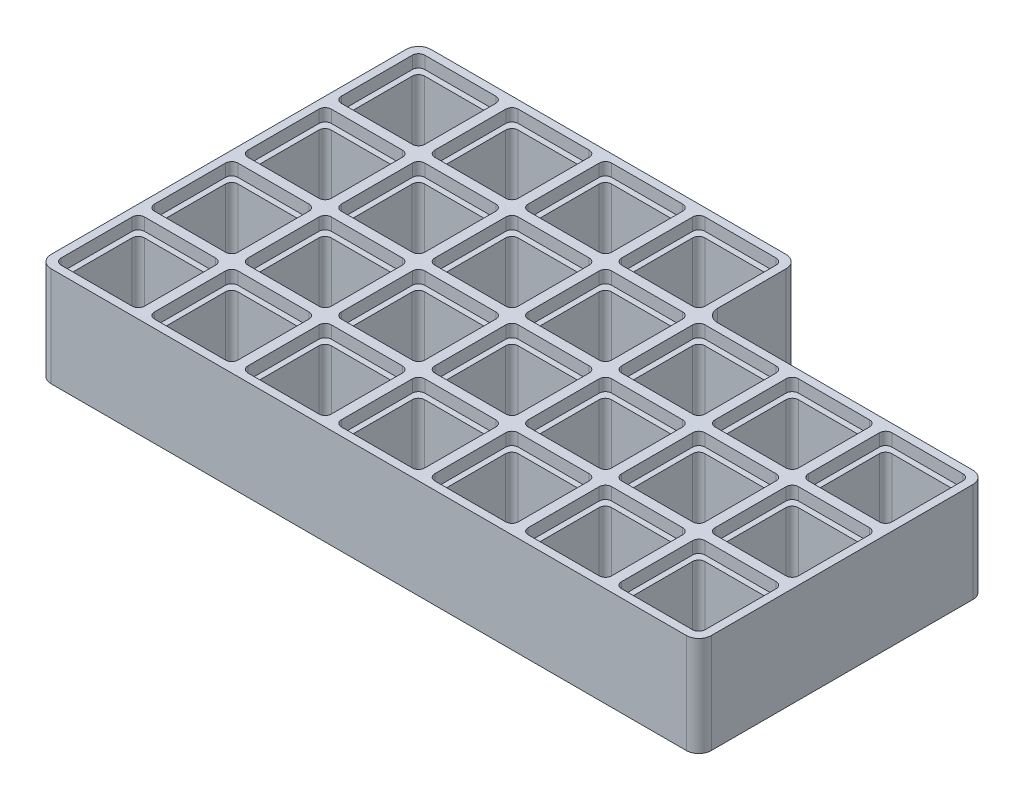
SolidWorks part; units mm, degrees
ref_plane "前视基准面" through (0, 0, 0) normal (0, 0, 1) x (1, 0, 0)
ref_plane "上视基准面" through (0, 0, 0) normal (0, 1, 0) x (1, 0, 0)
ref_plane "右视基准面" through (0, 0, 0) normal (1, 0, 0) x (0, 0, -1)
other "Configuration Table"
sketch "草图1" plane through (0, 0, 0) normal (0, 1, 0) x (1, 0, 0)
  line L0 (-45, 59) -> (-45, 48)
  line L1 (-104, 61) -> (-47, 61)
  line L2 (-106, 59) -> (-106, 2)
  line L3 (-104, 0) -> (-2, 0)
  line L4 (0, 44) -> (0, 2)
  line L9 (-43, 46) -> (-2, 46)
  arc A0 (-106, 2) -> (-104, 0) centre (-104, 2) ccw
  arc A1 (-2, 0) -> (0, 2) centre (-2, 2) ccw
  arc A3 (-104, 61) -> (-106, 59) centre (-104, 59) ccw
  arc A8 (-45, 48) -> (-43, 46) centre (-43, 48) ccw
  arc A9 (-2, 46) -> (0, 44) centre (-2, 44) cw
  arc A10 (-45, 59) -> (-47, 61) centre (-47, 59) ccw
  point P8 (-106, 0)
  point P11 (0, 0)
  point P12 (-45, 46)
  point P14 (0, 61)
  point P17 (-106, 61)
  point P22 (0, 46)
  point P25 (-45, 61)
  dimension "D3" = 2
  dimension "D6" = 2
  dimension "D1" = 106
  dimension "D2" = 61
  dimension "D4" = 45
  dimension "D5" = 15
extrude "凸台-拉伸1" add sketch "草图1" along normal blind 16
sketch "草图3" plane through (0, 0, 0) normal (0, -1, 0) x (1, 0, 0)
  line L0 (-106, -59) -> (-106, -2) construction
  line L1 (-102.8, -2.22) -> (-93.2, -2.22)
  line L2 (-103.8, -3.22) -> (-103.8, -12.78)
  line L3 (-102.8, -13.78) -> (-93.2, -13.78)
  line L4 (-92.2, -3.22) -> (-92.2, -12.78)
  line L5 (-103.8, -2.22) -> (-92.2, -13.78) construction
  line L6 (-103.8, -13.78) -> (-92.2, -2.22) construction
  line L7 (-104, 0) -> (-2, 0) construction
  line L8 (-103.8, -18.22) -> (-103.8, -27.78)
  line L9 (-102.8, -17.22) -> (-93.2, -17.22)
  line L10 (-92.2, -18.22) -> (-92.2, -27.78)
  line L11 (-102.8, -28.78) -> (-93.2, -28.78)
  line L12 (-103.8, -33.22) -> (-103.8, -42.78)
  line L13 (-102.8, -32.22) -> (-93.2, -32.22)
  line L14 (-92.2, -33.22) -> (-92.2, -42.78)
  line L15 (-102.8, -43.78) -> (-93.2, -43.78)
  line L16 (-103.8, -48.22) -> (-103.8, -57.78)
  line L17 (-102.8, -47.22) -> (-93.2, -47.22)
  line L18 (-92.2, -48.22) -> (-92.2, -57.78)
  line L19 (-102.8, -58.78) -> (-93.2, -58.78)
  line L20 (-87.8, -2.22) -> (-78.2, -2.22)
  line L21 (-77.2, -3.22) -> (-77.2, -12.78)
  line L22 (-87.8, -13.78) -> (-78.2, -13.78)
  line L23 (-88.8, -3.22) -> (-88.8, -12.78)
  line L24 (-87.8, -17.22) -> (-78.2, -17.22)
  line L25 (-77.2, -18.22) -> (-77.2, -27.78)
  line L26 (-87.8, -28.78) -> (-78.2, -28.78)
  line L27 (-88.8, -18.22) -> (-88.8, -27.78)
  line L28 (-88.8, -33.22) -> (-88.8, -42.78)
  line L29 (-87.8, -32.22) -> (-78.2, -32.22)
  line L30 (-77.2, -33.22) -> (-77.2, -42.78)
  line L31 (-87.8, -43.78) -> (-78.2, -43.78)
  line L32 (-72.8, -2.22) -> (-63.2, -2.22)
  line L33 (-62.2, -3.22) -> (-62.2, -12.78)
  line L34 (-72.8, -13.78) -> (-63.2, -13.78)
  line L35 (-73.8, -3.22) -> (-73.8, -12.78)
  line L36 (-72.8, -17.22) -> (-63.2, -17.22)
  line L37 (-62.2, -18.22) -> (-62.2, -27.78)
  line L38 (-72.8, -28.78) -> (-63.2, -28.78)
  line L39 (-73.8, -18.22) -> (-73.8, -27.78)
  line L40 (-73.8, -33.22) -> (-73.8, -42.78)
  line L41 (-72.8, -32.22) -> (-63.2, -32.22)
  line L42 (-62.2, -33.22) -> (-62.2, -42.78)
  line L43 (-72.8, -43.78) -> (-63.2, -43.78)
  line L44 (-57.8, -2.22) -> (-48.2, -2.22)
  line L45 (-47.2, -3.22) -> (-47.2, -12.78)
  line L46 (-57.8, -13.78) -> (-48.2, -13.78)
  line L47 (-58.8, -3.22) -> (-58.8, -12.78)
  line L48 (-57.8, -17.22) -> (-48.2, -17.22)
  line L49 (-47.2, -18.22) -> (-47.2, -27.78)
  line L50 (-57.8, -28.78) -> (-48.2, -28.78)
  line L51 (-58.8, -18.22) -> (-58.8, -27.78)
  line L52 (-58.8, -33.22) -> (-58.8, -42.78)
  line L53 (-57.8, -32.22) -> (-48.2, -32.22)
  line L54 (-47.2, -33.22) -> (-47.2, -42.78)
  line L55 (-57.8, -43.78) -> (-48.2, -43.78)
  line L56 (-42.8, -2.22) -> (-33.2, -2.22)
  line L57 (-32.2, -3.22) -> (-32.2, -12.78)
  line L58 (-42.8, -13.78) -> (-33.2, -13.78)
  line L59 (-43.8, -3.22) -> (-43.8, -12.78)
  line L60 (-42.8, -17.22) -> (-33.2, -17.22)
  line L61 (-32.2, -18.22) -> (-32.2, -27.78)
  line L62 (-42.8, -28.78) -> (-33.2, -28.78)
  line L63 (-43.8, -18.22) -> (-43.8, -27.78)
  line L64 (-43.8, -33.22) -> (-43.8, -42.78)
  line L65 (-42.8, -32.22) -> (-33.2, -32.22)
  line L66 (-32.2, -33.22) -> (-32.2, -42.78)
  line L67 (-42.8, -43.78) -> (-33.2, -43.78)
  line L68 (-27.8, -2.22) -> (-18.2, -2.22)
  line L69 (-17.2, -3.22) -> (-17.2, -12.78)
  line L70 (-27.8, -13.78) -> (-18.2, -13.78)
  line L71 (-28.8, -3.22) -> (-28.8, -12.78)
  line L72 (-27.8, -17.22) -> (-18.2, -17.22)
  line L73 (-17.2, -18.22) -> (-17.2, -27.78)
  line L74 (-27.8, -28.78) -> (-18.2, -28.78)
  line L75 (-28.8, -18.22) -> (-28.8, -27.78)
  line L76 (-28.8, -33.22) -> (-28.8, -42.78)
  line L77 (-27.8, -32.22) -> (-18.2, -32.22)
  line L78 (-17.2, -33.22) -> (-17.2, -42.78)
  line L79 (-27.8, -43.78) -> (-18.2, -43.78)
  line L80 (-12.8, -2.22) -> (-3.2, -2.22)
  line L81 (-2.2, -3.22) -> (-2.2, -12.78)
  line L82 (-12.8, -13.78) -> (-3.2, -13.78)
  line L83 (-13.8, -3.22) -> (-13.8, -12.78)
  line L84 (-12.8, -17.22) -> (-3.2, -17.22)
  line L85 (-2.2, -18.22) -> (-2.2, -27.78)
  line L86 (-12.8, -28.78) -> (-3.2, -28.78)
  line L87 (-13.8, -18.22) -> (-13.8, -27.78)
  line L88 (-13.8, -33.22) -> (-13.8, -42.78)
  line L89 (-12.8, -32.22) -> (-3.2, -32.22)
  line L90 (-2.2, -33.22) -> (-2.2, -42.78)
  line L91 (-12.8, -43.78) -> (-3.2, -43.78)
  line L92 (-87.8, -47.22) -> (-78.2, -47.22)
  line L93 (-77.2, -48.22) -> (-77.2, -57.78)
  line L94 (-87.8, -58.78) -> (-78.2, -58.78)
  line L95 (-88.8, -48.22) -> (-88.8, -57.78)
  line L96 (-72.8, -47.22) -> (-63.2, -47.22)
  line L97 (-62.2, -48.22) -> (-62.2, -57.78)
  line L98 (-72.8, -58.78) -> (-63.2, -58.78)
  line L99 (-73.8, -48.22) -> (-73.8, -57.78)
  line L100 (-57.8, -47.22) -> (-48.2, -47.22)
  line L101 (-47.2, -48.22) -> (-47.2, -57.78)
  line L102 (-57.8, -58.78) -> (-48.2, -58.78)
  line L103 (-58.8, -48.22) -> (-58.8, -57.78)
  arc A0 (-103.8, -12.78) -> (-102.8, -13.78) centre (-102.8, -12.78) ccw
  arc A1 (-93.2, -13.78) -> (-92.2, -12.78) centre (-93.2, -12.78) ccw
  arc A2 (-93.2, -2.22) -> (-92.2, -3.22) centre (-93.2, -3.22) cw
  arc A3 (-102.8, -2.22) -> (-103.8, -3.22) centre (-102.8, -3.22) ccw
  arc A4 (-102.8, -17.22) -> (-103.8, -18.22) centre (-102.8, -18.22) ccw
  arc A5 (-93.2, -17.22) -> (-92.2, -18.22) centre (-93.2, -18.22) cw
  arc A6 (-93.2, -28.78) -> (-92.2, -27.78) centre (-93.2, -27.78) ccw
  arc A7 (-103.8, -27.78) -> (-102.8, -28.78) centre (-102.8, -27.78) ccw
  arc A8 (-102.8, -32.22) -> (-103.8, -33.22) centre (-102.8, -33.22) ccw
  arc A9 (-93.2, -32.22) -> (-92.2, -33.22) centre (-93.2, -33.22) cw
  arc A10 (-93.2, -43.78) -> (-92.2, -42.78) centre (-93.2, -42.78) ccw
  arc A11 (-103.8, -42.78) -> (-102.8, -43.78) centre (-102.8, -42.78) ccw
  arc A12 (-102.8, -47.22) -> (-103.8, -48.22) centre (-102.8, -48.22) ccw
  arc A13 (-93.2, -47.22) -> (-92.2, -48.22) centre (-93.2, -48.22) cw
  arc A14 (-93.2, -58.78) -> (-92.2, -57.78) centre (-93.2, -57.78) ccw
  arc A15 (-103.8, -57.78) -> (-102.8, -58.78) centre (-102.8, -57.78) ccw
  arc A16 (-78.2, -2.22) -> (-77.2, -3.22) centre (-78.2, -3.22) cw
  arc A17 (-78.2, -13.78) -> (-77.2, -12.78) centre (-78.2, -12.78) ccw
  arc A18 (-88.8, -12.78) -> (-87.8, -13.78) centre (-87.8, -12.78) ccw
  arc A19 (-87.8, -2.22) -> (-88.8, -3.22) centre (-87.8, -3.22) ccw
  arc A20 (-87.8, -17.22) -> (-88.8, -18.22) centre (-87.8, -18.22) ccw
  arc A21 (-78.2, -17.22) -> (-77.2, -18.22) centre (-78.2, -18.22) cw
  arc A22 (-78.2, -28.78) -> (-77.2, -27.78) centre (-78.2, -27.78) ccw
  arc A23 (-88.8, -27.78) -> (-87.8, -28.78) centre (-87.8, -27.78) ccw
  arc A24 (-87.8, -32.22) -> (-88.8, -33.22) centre (-87.8, -33.22) ccw
  arc A25 (-78.2, -32.22) -> (-77.2, -33.22) centre (-78.2, -33.22) cw
  arc A26 (-78.2, -43.78) -> (-77.2, -42.78) centre (-78.2, -42.78) ccw
  arc A27 (-88.8, -42.78) -> (-87.8, -43.78) centre (-87.8, -42.78) ccw
  arc A28 (-63.2, -2.22) -> (-62.2, -3.22) centre (-63.2, -3.22) cw
  arc A29 (-63.2, -13.78) -> (-62.2, -12.78) centre (-63.2, -12.78) ccw
  arc A30 (-73.8, -12.78) -> (-72.8, -13.78) centre (-72.8, -12.78) ccw
  arc A31 (-72.8, -2.22) -> (-73.8, -3.22) centre (-72.8, -3.22) ccw
  arc A32 (-72.8, -17.22) -> (-73.8, -18.22) centre (-72.8, -18.22) ccw
  arc A33 (-63.2, -17.22) -> (-62.2, -18.22) centre (-63.2, -18.22) cw
  arc A34 (-63.2, -28.78) -> (-62.2, -27.78) centre (-63.2, -27.78) ccw
  arc A35 (-73.8, -27.78) -> (-72.8, -28.78) centre (-72.8, -27.78) ccw
  arc A36 (-72.8, -32.22) -> (-73.8, -33.22) centre (-72.8, -33.22) ccw
  arc A37 (-63.2, -32.22) -> (-62.2, -33.22) centre (-63.2, -33.22) cw
  arc A38 (-63.2, -43.78) -> (-62.2, -42.78) centre (-63.2, -42.78) ccw
  arc A39 (-73.8, -42.78) -> (-72.8, -43.78) centre (-72.8, -42.78) ccw
  arc A40 (-48.2, -2.22) -> (-47.2, -3.22) centre (-48.2, -3.22) cw
  arc A41 (-48.2, -13.78) -> (-47.2, -12.78) centre (-48.2, -12.78) ccw
  arc A42 (-58.8, -12.78) -> (-57.8, -13.78) centre (-57.8, -12.78) ccw
  arc A43 (-57.8, -2.22) -> (-58.8, -3.22) centre (-57.8, -3.22) ccw
  arc A44 (-57.8, -17.22) -> (-58.8, -18.22) centre (-57.8, -18.22) ccw
  arc A45 (-48.2, -17.22) -> (-47.2, -18.22) centre (-48.2, -18.22) cw
  arc A46 (-48.2, -28.78) -> (-47.2, -27.78) centre (-48.2, -27.78) ccw
  arc A47 (-58.8, -27.78) -> (-57.8, -28.78) centre (-57.8, -27.78) ccw
  arc A48 (-57.8, -32.22) -> (-58.8, -33.22) centre (-57.8, -33.22) ccw
  arc A49 (-48.2, -32.22) -> (-47.2, -33.22) centre (-48.2, -33.22) cw
  arc A50 (-48.2, -43.78) -> (-47.2, -42.78) centre (-48.2, -42.78) ccw
  arc A51 (-58.8, -42.78) -> (-57.8, -43.78) centre (-57.8, -42.78) ccw
  arc A52 (-33.2, -2.22) -> (-32.2, -3.22) centre (-33.2, -3.22) cw
  arc A53 (-33.2, -13.78) -> (-32.2, -12.78) centre (-33.2, -12.78) ccw
  arc A54 (-43.8, -12.78) -> (-42.8, -13.78) centre (-42.8, -12.78) ccw
  arc A55 (-42.8, -2.22) -> (-43.8, -3.22) centre (-42.8, -3.22) ccw
  arc A56 (-42.8, -17.22) -> (-43.8, -18.22) centre (-42.8, -18.22) ccw
  arc A57 (-33.2, -17.22) -> (-32.2, -18.22) centre (-33.2, -18.22) cw
  arc A58 (-33.2, -28.78) -> (-32.2, -27.78) centre (-33.2, -27.78) ccw
  arc A59 (-43.8, -27.78) -> (-42.8, -28.78) centre (-42.8, -27.78) ccw
  arc A60 (-42.8, -32.22) -> (-43.8, -33.22) centre (-42.8, -33.22) ccw
  arc A61 (-33.2, -32.22) -> (-32.2, -33.22) centre (-33.2, -33.22) cw
  arc A62 (-33.2, -43.78) -> (-32.2, -42.78) centre (-33.2, -42.78) ccw
  arc A63 (-43.8, -42.78) -> (-42.8, -43.78) centre (-42.8, -42.78) ccw
  arc A64 (-18.2, -2.22) -> (-17.2, -3.22) centre (-18.2, -3.22) cw
  arc A65 (-18.2, -13.78) -> (-17.2, -12.78) centre (-18.2, -12.78) ccw
  arc A66 (-28.8, -12.78) -> (-27.8, -13.78) centre (-27.8, -12.78) ccw
  arc A67 (-27.8, -2.22) -> (-28.8, -3.22) centre (-27.8, -3.22) ccw
  arc A68 (-27.8, -17.22) -> (-28.8, -18.22) centre (-27.8, -18.22) ccw
  arc A69 (-18.2, -17.22) -> (-17.2, -18.22) centre (-18.2, -18.22) cw
  arc A70 (-18.2, -28.78) -> (-17.2, -27.78) centre (-18.2, -27.78) ccw
  arc A71 (-28.8, -27.78) -> (-27.8, -28.78) centre (-27.8, -27.78) ccw
  arc A72 (-27.8, -32.22) -> (-28.8, -33.22) centre (-27.8, -33.22) ccw
  arc A73 (-18.2, -32.22) -> (-17.2, -33.22) centre (-18.2, -33.22) cw
  arc A74 (-18.2, -43.78) -> (-17.2, -42.78) centre (-18.2, -42.78) ccw
  arc A75 (-28.8, -42.78) -> (-27.8, -43.78) centre (-27.8, -42.78) ccw
  arc A76 (-3.2, -2.22) -> (-2.2, -3.22) centre (-3.2, -3.22) cw
  arc A77 (-3.2, -13.78) -> (-2.2, -12.78) centre (-3.2, -12.78) ccw
  arc A78 (-13.8, -12.78) -> (-12.8, -13.78) centre (-12.8, -12.78) ccw
  arc A79 (-12.8, -2.22) -> (-13.8, -3.22) centre (-12.8, -3.22) ccw
  arc A80 (-12.8, -17.22) -> (-13.8, -18.22) centre (-12.8, -18.22) ccw
  arc A81 (-3.2, -17.22) -> (-2.2, -18.22) centre (-3.2, -18.22) cw
  arc A82 (-3.2, -28.78) -> (-2.2, -27.78) centre (-3.2, -27.78) ccw
  arc A83 (-13.8, -27.78) -> (-12.8, -28.78) centre (-12.8, -27.78) ccw
  arc A84 (-12.8, -32.22) -> (-13.8, -33.22) centre (-12.8, -33.22) ccw
  arc A85 (-3.2, -32.22) -> (-2.2, -33.22) centre (-3.2, -33.22) cw
  arc A86 (-3.2, -43.78) -> (-2.2, -42.78) centre (-3.2, -42.78) ccw
  arc A87 (-13.8, -42.78) -> (-12.8, -43.78) centre (-12.8, -42.78) ccw
  arc A88 (-78.2, -47.22) -> (-77.2, -48.22) centre (-78.2, -48.22) cw
  arc A89 (-78.2, -58.78) -> (-77.2, -57.78) centre (-78.2, -57.78) ccw
  arc A90 (-88.8, -57.78) -> (-87.8, -58.78) centre (-87.8, -57.78) ccw
  arc A91 (-87.8, -47.22) -> (-88.8, -48.22) centre (-87.8, -48.22) ccw
  arc A92 (-63.2, -47.22) -> (-62.2, -48.22) centre (-63.2, -48.22) cw
  arc A93 (-63.2, -58.78) -> (-62.2, -57.78) centre (-63.2, -57.78) ccw
  arc A94 (-73.8, -57.78) -> (-72.8, -58.78) centre (-72.8, -57.78) ccw
  arc A95 (-72.8, -47.22) -> (-73.8, -48.22) centre (-72.8, -48.22) ccw
  arc A96 (-48.2, -47.22) -> (-47.2, -48.22) centre (-48.2, -48.22) cw
  arc A97 (-48.2, -58.78) -> (-47.2, -57.78) centre (-48.2, -57.78) ccw
  arc A98 (-58.8, -57.78) -> (-57.8, -58.78) centre (-57.8, -57.78) ccw
  arc A99 (-57.8, -47.22) -> (-58.8, -48.22) centre (-57.8, -48.22) ccw
  point P0 (-98, -8)
  dimension "D5" = 1
  dimension "D1" = 11.6
  dimension "D2" = 11.56
  dimension "D3" = 8
  dimension "D4" = 8
  dimension "D6" = 4
  dimension "D7" = 7
  dimension "D8" = 4
extrude "切除-拉伸2" cut sketch "草图3" against normal blind 18
sketch "草图2" plane through (0, 16, 0) normal (0, 1, 0) x (1, 0, 0)
  line L10 (-103.7, 29.7) -> (-92.3, 29.7)
  line L11 (-103.7, 14.7) -> (-92.3, 14.7)
  line L12 (-104.7, 13.7) -> (-104.7, 2.3)
  line L13 (-103.7, 1.3) -> (-92.3, 1.3)
  line L14 (-91.3, 13.7) -> (-91.3, 2.3)
  line L15 (-104.7, 14.7) -> (-91.3, 1.3) construction
  line L16 (-104.7, 1.3) -> (-91.3, 14.7) construction
  line L17 (-91.3, 28.7) -> (-91.3, 17.3)
  line L18 (-103.7, 16.3) -> (-92.3, 16.3)
  line L19 (-104.7, 28.7) -> (-104.7, 17.3)
  line L20 (-103.7, 44.7) -> (-92.3, 44.7)
  line L21 (-91.3, 43.7) -> (-91.3, 32.3)
  line L22 (-103.7, 31.3) -> (-92.3, 31.3)
  line L23 (-104.7, 43.7) -> (-104.7, 32.3)
  line L24 (-103.7, 59.7) -> (-92.3, 59.7)
  line L25 (-91.3, 58.7) -> (-91.3, 47.3)
  line L26 (-103.7, 46.3) -> (-92.3, 46.3)
  line L27 (-104.7, 58.7) -> (-104.7, 47.3)
  line L28 (-76.3, 13.7) -> (-76.3, 2.3)
  line L29 (-88.7, 14.7) -> (-77.3, 14.7)
  line L30 (-89.7, 13.7) -> (-89.7, 2.3)
  line L31 (-88.7, 1.3) -> (-77.3, 1.3)
  line L32 (-76.3, 28.7) -> (-76.3, 17.3)
  line L33 (-88.7, 16.3) -> (-77.3, 16.3)
  line L34 (-89.7, 28.7) -> (-89.7, 17.3)
  line L35 (-88.7, 29.7) -> (-77.3, 29.7)
  line L36 (-76.3, 43.7) -> (-76.3, 32.3)
  line L37 (-88.7, 44.7) -> (-77.3, 44.7)
  line L38 (-88.7, 31.3) -> (-77.3, 31.3)
  line L39 (-89.7, 43.7) -> (-89.7, 32.3)
  line L40 (-61.3, 13.7) -> (-61.3, 2.3)
  line L41 (-73.7, 14.7) -> (-62.3, 14.7)
  line L42 (-74.7, 13.7) -> (-74.7, 2.3)
  line L43 (-73.7, 1.3) -> (-62.3, 1.3)
  line L44 (-61.3, 28.7) -> (-61.3, 17.3)
  line L45 (-73.7, 16.3) -> (-62.3, 16.3)
  line L46 (-74.7, 28.7) -> (-74.7, 17.3)
  line L47 (-73.7, 29.7) -> (-62.3, 29.7)
  line L48 (-61.3, 43.7) -> (-61.3, 32.3)
  line L49 (-73.7, 44.7) -> (-62.3, 44.7)
  line L50 (-73.7, 31.3) -> (-62.3, 31.3)
  line L51 (-74.7, 43.7) -> (-74.7, 32.3)
  line L52 (-46.3, 13.7) -> (-46.3, 2.3)
  line L53 (-58.7, 14.7) -> (-47.3, 14.7)
  line L54 (-59.7, 13.7) -> (-59.7, 2.3)
  line L55 (-58.7, 1.3) -> (-47.3, 1.3)
  line L56 (-46.3, 28.7) -> (-46.3, 17.3)
  line L57 (-58.7, 16.3) -> (-47.3, 16.3)
  line L58 (-59.7, 28.7) -> (-59.7, 17.3)
  line L59 (-58.7, 29.7) -> (-47.3, 29.7)
  line L60 (-46.3, 43.7) -> (-46.3, 32.3)
  line L61 (-58.7, 44.7) -> (-47.3, 44.7)
  line L62 (-58.7, 31.3) -> (-47.3, 31.3)
  line L63 (-59.7, 43.7) -> (-59.7, 32.3)
  line L64 (-31.3, 13.7) -> (-31.3, 2.3)
  line L65 (-43.7, 14.7) -> (-32.3, 14.7)
  line L66 (-44.7, 13.7) -> (-44.7, 2.3)
  line L67 (-43.7, 1.3) -> (-32.3, 1.3)
  line L68 (-31.3, 28.7) -> (-31.3, 17.3)
  line L69 (-43.7, 16.3) -> (-32.3, 16.3)
  line L70 (-44.7, 28.7) -> (-44.7, 17.3)
  line L71 (-43.7, 29.7) -> (-32.3, 29.7)
  line L72 (-31.3, 43.7) -> (-31.3, 32.3)
  line L73 (-43.7, 44.7) -> (-32.3, 44.7)
  line L74 (-43.7, 31.3) -> (-32.3, 31.3)
  line L75 (-44.7, 43.7) -> (-44.7, 32.3)
  line L76 (-16.3, 13.7) -> (-16.3, 2.3)
  line L77 (-28.7, 14.7) -> (-17.3, 14.7)
  line L78 (-29.7, 13.7) -> (-29.7, 2.3)
  line L79 (-28.7, 1.3) -> (-17.3, 1.3)
  line L80 (-16.3, 28.7) -> (-16.3, 17.3)
  line L81 (-28.7, 16.3) -> (-17.3, 16.3)
  line L82 (-29.7, 28.7) -> (-29.7, 17.3)
  line L83 (-28.7, 29.7) -> (-17.3, 29.7)
  line L84 (-16.3, 43.7) -> (-16.3, 32.3)
  line L85 (-28.7, 44.7) -> (-17.3, 44.7)
  line L86 (-28.7, 31.3) -> (-17.3, 31.3)
  line L87 (-29.7, 43.7) -> (-29.7, 32.3)
  line L88 (-1.3, 13.7) -> (-1.3, 2.3)
  line L89 (-13.7, 14.7) -> (-2.3, 14.7)
  line L90 (-14.7, 13.7) -> (-14.7, 2.3)
  line L91 (-13.7, 1.3) -> (-2.3, 1.3)
  line L92 (-1.3, 28.7) -> (-1.3, 17.3)
  line L93 (-13.7, 16.3) -> (-2.3, 16.3)
  line L94 (-14.7, 28.7) -> (-14.7, 17.3)
  line L95 (-13.7, 29.7) -> (-2.3, 29.7)
  line L96 (-1.3, 43.7) -> (-1.3, 32.3)
  line L97 (-13.7, 44.7) -> (-2.3, 44.7)
  line L98 (-13.7, 31.3) -> (-2.3, 31.3)
  line L99 (-14.7, 43.7) -> (-14.7, 32.3)
  line L100 (-76.3, 58.7) -> (-76.3, 47.3)
  line L101 (-88.7, 46.3) -> (-77.3, 46.3)
  line L102 (-89.7, 58.7) -> (-89.7, 47.3)
  line L103 (-88.7, 59.7) -> (-77.3, 59.7)
  line L104 (-61.3, 58.7) -> (-61.3, 47.3)
  line L105 (-73.7, 46.3) -> (-62.3, 46.3)
  line L106 (-74.7, 58.7) -> (-74.7, 47.3)
  line L107 (-73.7, 59.7) -> (-62.3, 59.7)
  line L108 (-46.3, 58.7) -> (-46.3, 47.3)
  line L109 (-58.7, 46.3) -> (-47.3, 46.3)
  line L110 (-59.7, 58.7) -> (-59.7, 47.3)
  line L111 (-58.7, 59.7) -> (-47.3, 59.7)
  line L112 (-106, 59) -> (-106, 2) construction
  line L113 (-104, 0) -> (-2, 0) construction
  arc A6 (-103.7, 14.7) -> (-104.7, 13.7) centre (-103.7, 13.7) ccw
  arc A7 (-104.7, 2.3) -> (-103.7, 1.3) centre (-103.7, 2.3) ccw
  arc A8 (-92.3, 1.3) -> (-91.3, 2.3) centre (-92.3, 2.3) ccw
  arc A9 (-92.3, 14.7) -> (-91.3, 13.7) centre (-92.3, 13.7) cw
  arc A10 (-103.7, 29.7) -> (-104.7, 28.7) centre (-103.7, 28.7) ccw
  arc A11 (-92.3, 29.7) -> (-91.3, 28.7) centre (-92.3, 28.7) cw
  arc A12 (-92.3, 16.3) -> (-91.3, 17.3) centre (-92.3, 17.3) ccw
  arc A13 (-104.7, 17.3) -> (-103.7, 16.3) centre (-103.7, 17.3) ccw
  arc A14 (-103.7, 44.7) -> (-104.7, 43.7) centre (-103.7, 43.7) ccw
  arc A15 (-92.3, 44.7) -> (-91.3, 43.7) centre (-92.3, 43.7) cw
  arc A16 (-92.3, 31.3) -> (-91.3, 32.3) centre (-92.3, 32.3) ccw
  arc A17 (-104.7, 32.3) -> (-103.7, 31.3) centre (-103.7, 32.3) ccw
  arc A18 (-103.7, 59.7) -> (-104.7, 58.7) centre (-103.7, 58.7) ccw
  arc A19 (-92.3, 59.7) -> (-91.3, 58.7) centre (-92.3, 58.7) cw
  arc A20 (-92.3, 46.3) -> (-91.3, 47.3) centre (-92.3, 47.3) ccw
  arc A21 (-104.7, 47.3) -> (-103.7, 46.3) centre (-103.7, 47.3) ccw
  arc A22 (-77.3, 14.7) -> (-76.3, 13.7) centre (-77.3, 13.7) cw
  arc A23 (-88.7, 14.7) -> (-89.7, 13.7) centre (-88.7, 13.7) ccw
  arc A24 (-89.7, 2.3) -> (-88.7, 1.3) centre (-88.7, 2.3) ccw
  arc A25 (-77.3, 1.3) -> (-76.3, 2.3) centre (-77.3, 2.3) ccw
  arc A26 (-77.3, 16.3) -> (-76.3, 17.3) centre (-77.3, 17.3) ccw
  arc A27 (-89.7, 17.3) -> (-88.7, 16.3) centre (-88.7, 17.3) ccw
  arc A28 (-88.7, 29.7) -> (-89.7, 28.7) centre (-88.7, 28.7) ccw
  arc A29 (-77.3, 29.7) -> (-76.3, 28.7) centre (-77.3, 28.7) cw
  arc A30 (-77.3, 44.7) -> (-76.3, 43.7) centre (-77.3, 43.7) cw
  arc A31 (-77.3, 31.3) -> (-76.3, 32.3) centre (-77.3, 32.3) ccw
  arc A32 (-89.7, 32.3) -> (-88.7, 31.3) centre (-88.7, 32.3) ccw
  arc A33 (-88.7, 44.7) -> (-89.7, 43.7) centre (-88.7, 43.7) ccw
  arc A34 (-62.3, 14.7) -> (-61.3, 13.7) centre (-62.3, 13.7) cw
  arc A35 (-73.7, 14.7) -> (-74.7, 13.7) centre (-73.7, 13.7) ccw
  arc A36 (-74.7, 2.3) -> (-73.7, 1.3) centre (-73.7, 2.3) ccw
  arc A37 (-62.3, 1.3) -> (-61.3, 2.3) centre (-62.3, 2.3) ccw
  arc A38 (-62.3, 16.3) -> (-61.3, 17.3) centre (-62.3, 17.3) ccw
  arc A39 (-74.7, 17.3) -> (-73.7, 16.3) centre (-73.7, 17.3) ccw
  arc A40 (-73.7, 29.7) -> (-74.7, 28.7) centre (-73.7, 28.7) ccw
  arc A41 (-62.3, 29.7) -> (-61.3, 28.7) centre (-62.3, 28.7) cw
  arc A42 (-62.3, 44.7) -> (-61.3, 43.7) centre (-62.3, 43.7) cw
  arc A43 (-62.3, 31.3) -> (-61.3, 32.3) centre (-62.3, 32.3) ccw
  arc A44 (-74.7, 32.3) -> (-73.7, 31.3) centre (-73.7, 32.3) ccw
  arc A45 (-73.7, 44.7) -> (-74.7, 43.7) centre (-73.7, 43.7) ccw
  arc A46 (-47.3, 14.7) -> (-46.3, 13.7) centre (-47.3, 13.7) cw
  arc A47 (-58.7, 14.7) -> (-59.7, 13.7) centre (-58.7, 13.7) ccw
  arc A48 (-59.7, 2.3) -> (-58.7, 1.3) centre (-58.7, 2.3) ccw
  arc A49 (-47.3, 1.3) -> (-46.3, 2.3) centre (-47.3, 2.3) ccw
  arc A50 (-47.3, 16.3) -> (-46.3, 17.3) centre (-47.3, 17.3) ccw
  arc A51 (-59.7, 17.3) -> (-58.7, 16.3) centre (-58.7, 17.3) ccw
  arc A52 (-58.7, 29.7) -> (-59.7, 28.7) centre (-58.7, 28.7) ccw
  arc A53 (-47.3, 29.7) -> (-46.3, 28.7) centre (-47.3, 28.7) cw
  arc A54 (-47.3, 44.7) -> (-46.3, 43.7) centre (-47.3, 43.7) cw
  arc A55 (-47.3, 31.3) -> (-46.3, 32.3) centre (-47.3, 32.3) ccw
  arc A56 (-59.7, 32.3) -> (-58.7, 31.3) centre (-58.7, 32.3) ccw
  arc A57 (-58.7, 44.7) -> (-59.7, 43.7) centre (-58.7, 43.7) ccw
  arc A58 (-32.3, 14.7) -> (-31.3, 13.7) centre (-32.3, 13.7) cw
  arc A59 (-43.7, 14.7) -> (-44.7, 13.7) centre (-43.7, 13.7) ccw
  arc A60 (-44.7, 2.3) -> (-43.7, 1.3) centre (-43.7, 2.3) ccw
  arc A61 (-32.3, 1.3) -> (-31.3, 2.3) centre (-32.3, 2.3) ccw
  arc A62 (-32.3, 16.3) -> (-31.3, 17.3) centre (-32.3, 17.3) ccw
  arc A63 (-44.7, 17.3) -> (-43.7, 16.3) centre (-43.7, 17.3) ccw
  arc A64 (-43.7, 29.7) -> (-44.7, 28.7) centre (-43.7, 28.7) ccw
  arc A65 (-32.3, 29.7) -> (-31.3, 28.7) centre (-32.3, 28.7) cw
  arc A66 (-32.3, 44.7) -> (-31.3, 43.7) centre (-32.3, 43.7) cw
  arc A67 (-32.3, 31.3) -> (-31.3, 32.3) centre (-32.3, 32.3) ccw
  arc A68 (-44.7, 32.3) -> (-43.7, 31.3) centre (-43.7, 32.3) ccw
  arc A69 (-43.7, 44.7) -> (-44.7, 43.7) centre (-43.7, 43.7) ccw
  arc A70 (-17.3, 14.7) -> (-16.3, 13.7) centre (-17.3, 13.7) cw
  arc A71 (-28.7, 14.7) -> (-29.7, 13.7) centre (-28.7, 13.7) ccw
  arc A72 (-29.7, 2.3) -> (-28.7, 1.3) centre (-28.7, 2.3) ccw
  arc A73 (-17.3, 1.3) -> (-16.3, 2.3) centre (-17.3, 2.3) ccw
  arc A74 (-17.3, 16.3) -> (-16.3, 17.3) centre (-17.3, 17.3) ccw
  arc A75 (-29.7, 17.3) -> (-28.7, 16.3) centre (-28.7, 17.3) ccw
  arc A76 (-28.7, 29.7) -> (-29.7, 28.7) centre (-28.7, 28.7) ccw
  arc A77 (-17.3, 29.7) -> (-16.3, 28.7) centre (-17.3, 28.7) cw
  arc A78 (-17.3, 44.7) -> (-16.3, 43.7) centre (-17.3, 43.7) cw
  arc A79 (-17.3, 31.3) -> (-16.3, 32.3) centre (-17.3, 32.3) ccw
  arc A80 (-29.7, 32.3) -> (-28.7, 31.3) centre (-28.7, 32.3) ccw
  arc A81 (-28.7, 44.7) -> (-29.7, 43.7) centre (-28.7, 43.7) ccw
  arc A82 (-2.3, 14.7) -> (-1.3, 13.7) centre (-2.3, 13.7) cw
  arc A83 (-13.7, 14.7) -> (-14.7, 13.7) centre (-13.7, 13.7) ccw
  arc A84 (-14.7, 2.3) -> (-13.7, 1.3) centre (-13.7, 2.3) ccw
  arc A85 (-2.3, 1.3) -> (-1.3, 2.3) centre (-2.3, 2.3) ccw
  arc A86 (-2.3, 16.3) -> (-1.3, 17.3) centre (-2.3, 17.3) ccw
  arc A87 (-14.7, 17.3) -> (-13.7, 16.3) centre (-13.7, 17.3) ccw
  arc A88 (-13.7, 29.7) -> (-14.7, 28.7) centre (-13.7, 28.7) ccw
  arc A89 (-2.3, 29.7) -> (-1.3, 28.7) centre (-2.3, 28.7) cw
  arc A90 (-2.3, 44.7) -> (-1.3, 43.7) centre (-2.3, 43.7) cw
  arc A91 (-2.3, 31.3) -> (-1.3, 32.3) centre (-2.3, 32.3) ccw
  arc A92 (-14.7, 32.3) -> (-13.7, 31.3) centre (-13.7, 32.3) ccw
  arc A93 (-13.7, 44.7) -> (-14.7, 43.7) centre (-13.7, 43.7) ccw
  arc A94 (-77.3, 46.3) -> (-76.3, 47.3) centre (-77.3, 47.3) ccw
  arc A95 (-89.7, 47.3) -> (-88.7, 46.3) centre (-88.7, 47.3) ccw
  arc A96 (-88.7, 59.7) -> (-89.7, 58.7) centre (-88.7, 58.7) ccw
  arc A97 (-77.3, 59.7) -> (-76.3, 58.7) centre (-77.3, 58.7) cw
  arc A98 (-62.3, 46.3) -> (-61.3, 47.3) centre (-62.3, 47.3) ccw
  arc A99 (-74.7, 47.3) -> (-73.7, 46.3) centre (-73.7, 47.3) ccw
  arc A100 (-73.7, 59.7) -> (-74.7, 58.7) centre (-73.7, 58.7) ccw
  arc A101 (-62.3, 59.7) -> (-61.3, 58.7) centre (-62.3, 58.7) cw
  arc A102 (-47.3, 46.3) -> (-46.3, 47.3) centre (-47.3, 47.3) ccw
  arc A103 (-59.7, 47.3) -> (-58.7, 46.3) centre (-58.7, 47.3) ccw
  arc A104 (-58.7, 59.7) -> (-59.7, 58.7) centre (-58.7, 58.7) ccw
  arc A105 (-47.3, 59.7) -> (-46.3, 58.7) centre (-47.3, 58.7) cw
  point P19 (0, 0)
  point P28 (-98, 8)
  dimension "D1" = 8
  dimension "D6" = 1
  dimension "D2" = 13.4
  dimension "D3" = 13.4
  dimension "D4" = 8
  dimension "D7" = 4
  dimension "D8" = 7
  dimension "D9" = 4
extrude "切除-拉伸3" cut sketch "草图2" against normal blind 2
sketch "草图4" plane through (0, 0, 0) normal (0, -1, 0) x (1, 0, 0)
  line L0 (-90.5, -13.2197) -> (-90.5, -15.5) construction
  line L1 (-90.5, -15.5) -> (-87.6804, -15.5) construction
  line L2 (-90.5, -41.2862) -> (-90.5, -45.5) construction
  line L3 (-90.5, -45.5) -> (-86.9903, -45.5) construction
  line L4 (-15.5, -12.7755) -> (-15.5, -15.5) construction
  line L5 (-15.5, -15.5) -> (-12.4454, -15.5) construction
  line L6 (-15.5, -28.1887) -> (-15.5, -30.5) construction
  line L7 (-15.5, -30.5) -> (-12.0086, -30.5) construction
  line L8 (-87.8, -13.78) -> (-78.2, -13.78) construction
  line L9 (-78.2, -17.22) -> (-87.8, -17.22) construction
  line L10 (-92.2, -12.78) -> (-92.2, -3.22) construction
  line L11 (-88.8, -3.22) -> (-88.8, -12.78) construction
  line L12 (-88.8, -33.22) -> (-88.8, -42.78) construction
  line L13 (-92.2, -42.78) -> (-92.2, -33.22) construction
  line L14 (-87.8, -43.78) -> (-78.2, -43.78) construction
  line L15 (-78.2, -47.22) -> (-87.8, -47.22) construction
  line L16 (-12.8, -28.78) -> (-3.2, -28.78) construction
  line L17 (-3.2, -32.22) -> (-12.8, -32.22) construction
  line L18 (-17.2, -27.78) -> (-17.2, -18.22) construction
  line L19 (-13.8, -18.22) -> (-13.8, -27.78) construction
  line L20 (-12.8, -13.78) -> (-3.2, -13.78) construction
  line L21 (-3.2, -17.22) -> (-12.8, -17.22) construction
  line L22 (-17.2, -12.78) -> (-17.2, -3.22) construction
  line L23 (-13.8, -3.22) -> (-13.8, -12.78) construction
  circle A0 centre (-90.5, -15.5) radius 1.5
  circle A1 centre (-90.5, -45.5) radius 1.5
  circle A4 centre (-15.5, -15.5) radius 1.5
  circle A5 centre (-15.5, -30.5) radius 1.5
  dimension "D1" = 3
extrude "凸台-拉伸2" add sketch "草图4" along normal blind 1.6
